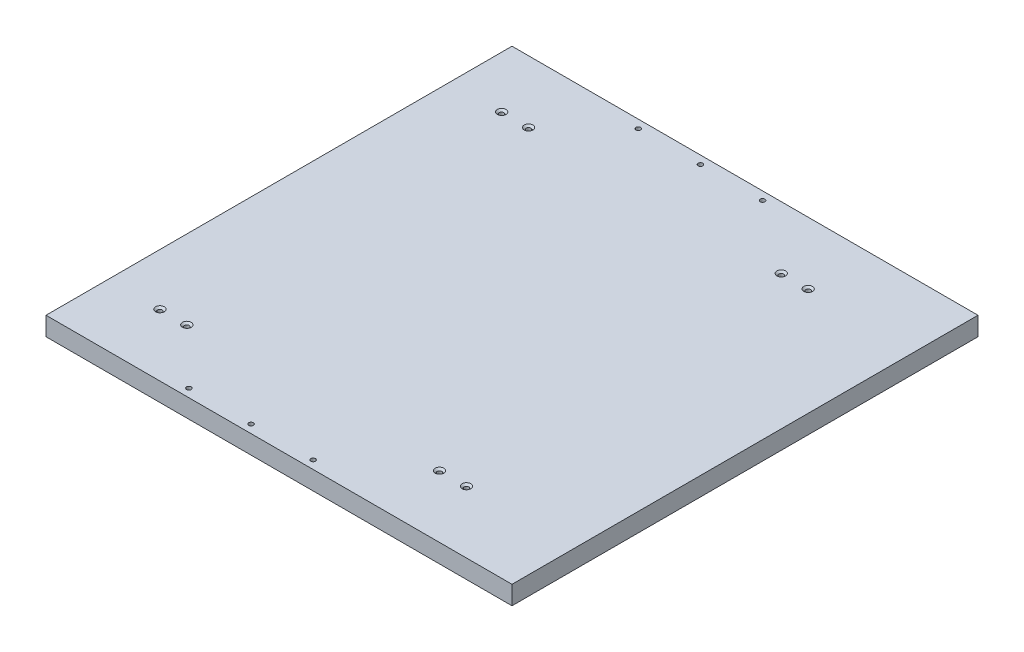
SolidWorks part; units mm, degrees
ref_plane "Front Plane" through (0, 0, 0) normal (0, 0, 1) x (1, 0, 0)
ref_plane "Top Plane" through (0, 0, 0) normal (0, 1, 0) x (1, 0, 0)
ref_plane "Right Plane" through (0, 0, 0) normal (1, 0, 0) x (0, 0, -1)
other "Bounding Box"
ref_plane "Default Plane" through (-225, 9, -225) normal (0, 0, 1) x (1, 0, 0)
sketch "Sketch1" plane through (0, 0, 0) normal (0, 1, 0) x (1, 0, 0)
  line L0 (-225, 225) -> (225, -225) construction
  line L1 (-225, 225) -> (225, 225)
  line L2 (-225, 225) -> (-225, -225)
  line L3 (-225, -225) -> (225, -225)
  line L4 (225, 225) -> (225, -225)
  line L5 (225, 225) -> (-225, -225) construction
  point P0 (0, 0)
  dimension "D1" = 450
  dimension "D2" = 450
extrude "Boss-Extrude1" add sketch "Sketch1" along normal mid plane 18 contours L4 L3 L2 L1
hole_wizard "CSK for #8 Flat Head Machine Screw (100)1" positions "Sketch2" profile "Sketch3" countersink size "#8" standard "ANSI Inch" end condition through all
sketch "Sketch2" plane through (-75, -9, 0) normal (0, -1, 0) x (0, 0, -1)
  line L3 (-225, -150) -> (-225, 300) construction
  line L4 (225, 300) -> (-225, 300) construction
  line L5 (-225, 75) -> (225, 75) construction
  line L6 (225, -150) -> (225, 300) construction
  point P9 (-217, 40)
  point P14 (-217, -20)
  point P27 (-217, 100)
  dimension "D1" = 8
  dimension "D2" = 60
  dimension "D3" = 60
  dimension "D4" = 200
sketch "Sketch3" plane through (-35, -9, 217) normal (1, 0, 0) x (0, 0, -1)
  line L0 (0, 0) -> (0, 18)
  line L1 (0, 18) -> (2.2479, 18)
  line L2 (2.2479, 18) -> (2.2479, 1.6518)
  line L3 (2.2479, 1.6518) -> (4.2164, 0)
  line L5 (4.2164, 0) -> (0, 0)
  line L6 (-2.2479, 1.6518) -> (-4.2164, 0) construction
  line L11 (0, -6.35) -> (0, 107.95) construction
  dimension "Thru Hole Dia." = 4.4958
  dimension "Thru Hole Depth" = 18
  dimension "Near C'Sink Dia." = 8.4328
  dimension "Near C'Sink Angle" = 100
mirror "Mirror1" about plane through (0, 0, 0) normal (0, 0, 1) of "CSK for #8 Flat Head Machine Screw (100)1"
hole_wizard "CSK for #8 Flat Head Machine Screw (100)2" positions "Sketch6" profile "Sketch5" countersink size "#8" standard "ANSI Inch" end condition through all
sketch "Sketch6" plane through (0, 9, 0) normal (0, -1, 0) x (-1, 0, 0)
  line L0 (149, -165) -> (175, -165) construction
  line L2 (225, 225) -> (225, -225) construction
  line L3 (225, -225) -> (-225, -225) construction
  point P0 (175, -165)
  point P2 (149, -165)
  dimension "D1" = 26
  dimension "D2" = 50
  dimension "D3" = 60
sketch "Sketch5" plane through (-175, 9, 165) normal (1, 0, 0) x (0, 0, 1)
  line L0 (0, 0) -> (0, 18)
  line L1 (0, 18) -> (2.2479, 18)
  line L2 (2.2479, 18) -> (2.2479, 1.6518)
  line L3 (2.2479, 1.6518) -> (4.2164, 0)
  line L5 (4.2164, 0) -> (0, 0)
  line L6 (-2.2479, 1.6518) -> (-4.2164, 0) construction
  line L11 (0, -6.35) -> (0, 107.95) construction
  dimension "Thru Hole Dia." = 4.4958
  dimension "Thru Hole Depth" = 18
  dimension "Near C'Sink Dia." = 8.4328
  dimension "Near C'Sink Angle" = 100
pattern_linear "LPattern1" count 2 spacing 270 along (1, 0, 0) of "CSK for #8 Flat Head Machine Screw (100)2"
mirror "Mirror2" about plane through (0, 0, 0) normal (0, 0, 1) of "LPattern1", "CSK for #8 Flat Head Machine Screw (100)2"
